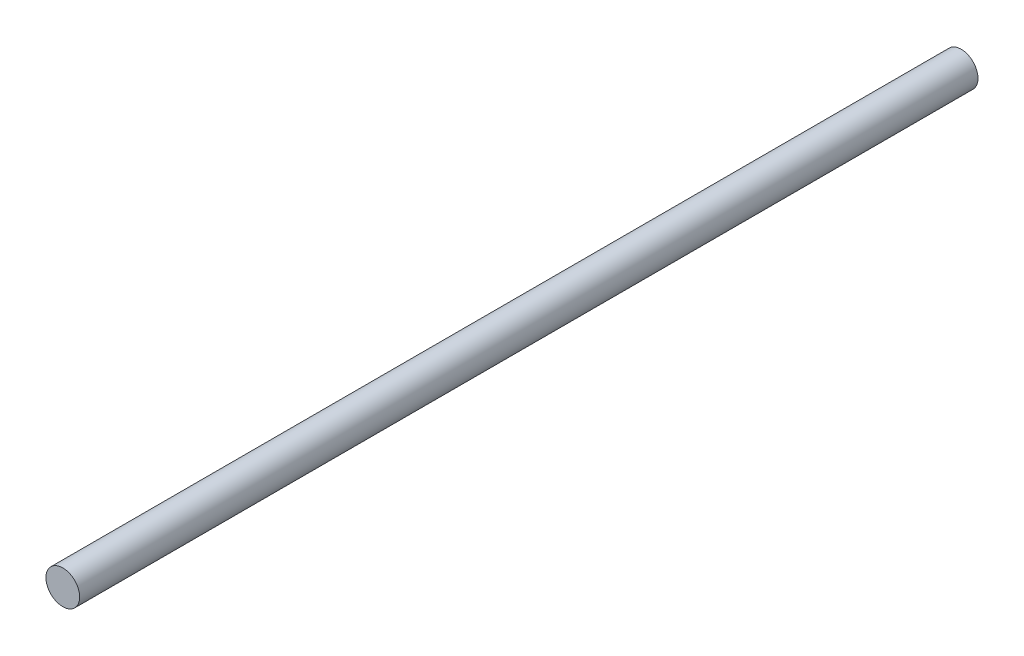
SolidWorks part; units mm, degrees
ref_plane "Спереди" through (0, 0, 0) normal (0, 0, 1) x (1, 0, 0)
ref_plane "Сверху" through (0, 0, 0) normal (0, 1, 0) x (1, 0, 0)
ref_plane "Справа" through (0, 0, 0) normal (1, 0, 0) x (0, 0, -1)
sketch "Эскиз1" plane through (0, 0, 0) normal (0, 0, 1) x (1, 0, 0)
  circle A0 centre (0, 0) radius 6
  dimension "D1" = 12
extrude "Бобышка-Вытянуть1" add sketch "Эскиз1" along normal blind 320
